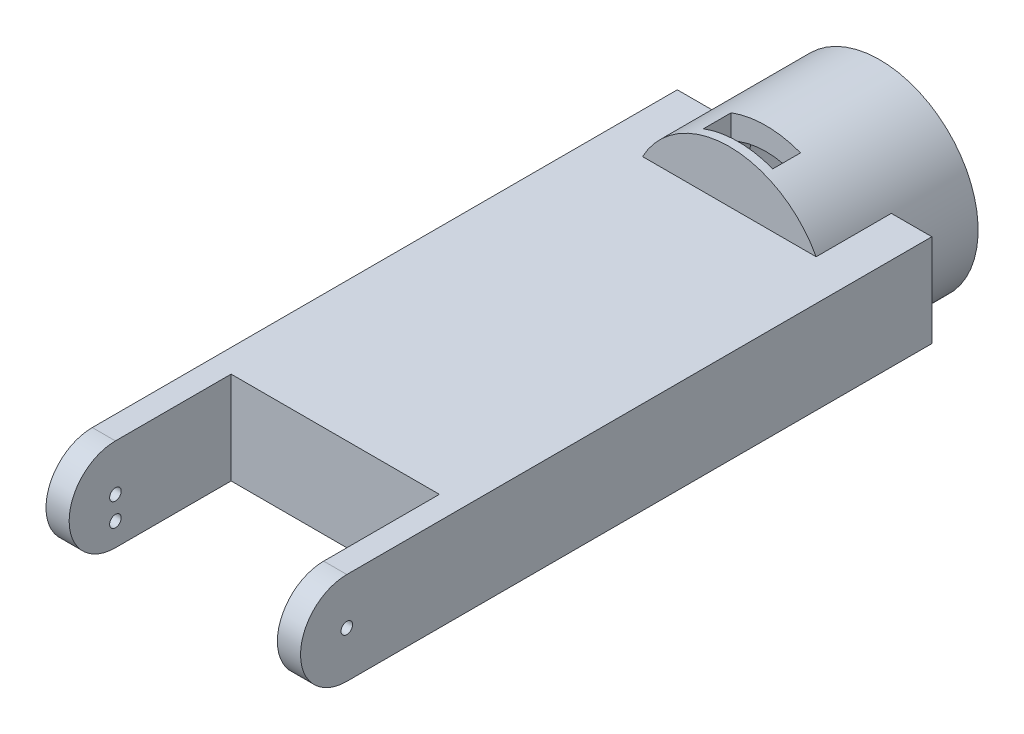
SolidWorks part; units mm, degrees
ref_plane "前视基准面" through (0, 0, 0) normal (0, 0, 1) x (1, 0, 0)
ref_plane "上视基准面" through (0, 0, 0) normal (0, 1, 0) x (1, 0, 0)
ref_plane "右视基准面" through (0, 0, 0) normal (1, 0, 0) x (0, 0, -1)
sketch "草图1" plane through (0, 0, 0) normal (1, 0, 0) x (0, 0, -1)
  line L0 (0, 0) -> (260, 0) construction
  line L1 (0, 20) -> (260, 20)
  line L2 (0, -20) -> (260, -20)
  arc A0 (0, 20) -> (0, -20) centre (0, 0) ccw
  arc A1 (260, -20) -> (260, 20) centre (260, 0) ccw
  point P3 (130, 0)
  point P8 (-20, 0)
  point P9 (280, 0)
  dimension "D2" = 20
  dimension "D1" = 300
extrude "凸台-拉伸1" add sketch "草图1" along normal blind 110
sketch "草图2" plane through (0, 20, 0) normal (0, 1, 0) x (1, 0, 0)
  line L0 (55, 260) -> (55, -142.7048) construction
  line L1 (110, 260) -> (0, 260) construction
  line L2 (10, 50) -> (100, 50)
  line L3 (100, 50) -> (100, -20)
  line L4 (100, -20) -> (10, -20)
  line L5 (10, -20) -> (10, 50)
  line L7 (0, -20) -> (129.5487, -20) construction
  dimension "D1" = 90
  dimension "D2" = 70
extrude "切除-拉伸2" cut sketch "草图2" against normal through all both and the other way through all
sketch "草图3" plane through (0, 0, 0) normal (-1, 0, 0) x (0, 0, 1)
  circle A0 centre (0, 0) radius 2.5
  dimension "D1" = 5
extrude "切除-拉伸3" cut sketch "草图3" against normal through all both and the other way through all
sketch "草图4" plane through (110, 0, 0) normal (1, 0, 0) x (0, 0, -1)
  line L0 (252.8151, 20) -> (252.8151, -20)
  line L1 (260, 20) -> (0, 20) construction
  line L2 (0, -20) -> (260, -20) construction
  line L3 (252.8151, -20) -> (282.4834, -20)
  line L4 (282.4834, -20) -> (282.4834, 20)
  line L5 (282.4834, 20) -> (252.8151, 20)
extrude "切除-拉伸4" cut sketch "草图4" against normal through all both and the other way through all
sketch "草图5" plane through (0, 0, -252.8151) normal (0, 0, -1) x (-1, 0, 0)
  line L0 (-55, 20) -> (-55, -36.729) construction
  line L1 (0, 20) -> (-110, 20) construction
  line L2 (0, 0) -> (-64.4487, 0) construction
  line L3 (0, 20) -> (0, -20) construction
  circle A0 centre (-55, 0) radius 42.5
  dimension "D1" = 85
extrude "凸台-拉伸2" add sketch "草图5" along normal mid plane 65
sketch "草图6" plane through (0, 0, -285.3151) normal (0, 0, -1) x (-1, 0, 0)
  line L0 (-55, 42.5) -> (-55, -42.5) construction
  line L1 (-97.5, 0) -> (35.2634, 0) construction
  circle A0 centre (-55, 0) radius 42.5 construction
  circle A1 centre (-55, 0) radius 38.01
  dimension "D1" = 76.02
extrude "切除-拉伸6" cut sketch "草图6" against normal blind 23.7
sketch "草图7" plane through (0, 0, -261.6151) normal (0, 0, -1) x (-1, 0, 0)
  line L0 (-55, 38.01) -> (-55, -69.1638) construction
  line L1 (-16.99, 0) -> (-85.8755, 0) construction
  circle A0 centre (-55, 0) radius 38.01 construction
  circle A1 centre (-55, 0) radius 38.01 construction
  circle A2 centre (-55, 0) radius 32.8
  dimension "D1" = 65.6
extrude "切除-拉伸7" cut sketch "草图7" against normal blind 38.3
sketch "草图9" plane through (0, 0, -261.6151) normal (0, 0, -1) x (-1, 0, 0)
  line L0 (-55, -42.5) -> (-55, 57.0292) construction
  line L1 (-93.01, 0) -> (67.301, 0) construction
  circle A0 centre (-55, 0) radius 42.5 construction
  circle A1 centre (-55, 0) radius 38.01 construction
  circle A2 centre (-55, 0) radius 38.01 construction
  circle A3 centre (-55, 0) radius 34.5 construction
  circle A4 centre (-55, 34.5) radius 1.25
  circle A5 centre (-41.7974, 31.8738) radius 1.25
  circle A6 centre (-30.6048, 24.3952) radius 1.25
  circle A7 centre (-23.1262, 13.2026) radius 1.25
  circle A8 centre (-20.5, 0) radius 1.25
  circle A9 centre (-23.1262, -13.2026) radius 1.25
  circle A10 centre (-30.6048, -24.3952) radius 1.25
  circle A11 centre (-41.7974, -31.8738) radius 1.25
  circle A12 centre (-55, -34.5) radius 1.25
  circle A13 centre (-68.2026, -31.8738) radius 1.25
  circle A14 centre (-79.3952, -24.3952) radius 1.25
  circle A15 centre (-86.8738, -13.2026) radius 1.25
  circle A16 centre (-89.5, 0) radius 1.25
  circle A17 centre (-86.8738, 13.2026) radius 1.25
  circle A18 centre (-79.3952, 24.3952) radius 1.25
  circle A19 centre (-68.2026, 31.8738) radius 1.25
  point P50 (-55, 0)
  dimension "D1" = 69
  dimension "D2" = 2.5
  dimension "D3" = 16
extrude "切除-拉伸8" cut sketch "草图9" against normal blind 5
ref_plane "基准面1" through (0, 50, 0) normal (0, 1, 0) x (1, 0, 0)
sketch "草图10" plane through (0, 50, 0) normal (0, 1, 0) x (1, 0, 0)
  line L0 (55, 285.3151) -> (55, -14.1286) construction
  line L1 (97.5, 285.3151) -> (12.5, 285.3151) construction
  line L2 (40, 236.0783) -> (40, 224.0783)
  line L4 (40, 224.0783) -> (70, 224.0783)
  line L5 (70, 224.0783) -> (70, 236.0783)
  line L6 (70, 236.0783) -> (40, 236.0783)
  dimension "D1" = 12
  dimension "D2" = 30
extrude "切除-拉伸11" cut sketch "草图10" against normal through all both and the other way through all
sketch "草图11" plane through (110, 0, 0) normal (1, 0, 0) x (0, 0, -1)
  line L0 (0, 0) -> (10, 0) construction
  circle A0 centre (10, 0) radius 2.5
  dimension "D1" = 5
  dimension "D2" = 10
sketch "草图12" plane through (0, 0, 0) normal (-1, 0, 0) x (0, 0, 1)
  line L0 (0, -10) -> (0, 0) construction
  circle A3 centre (0, -10) radius 2.5
  dimension "D1" = 10
extrude "切除-拉伸13" cut sketch "草图12" against normal blind 10
